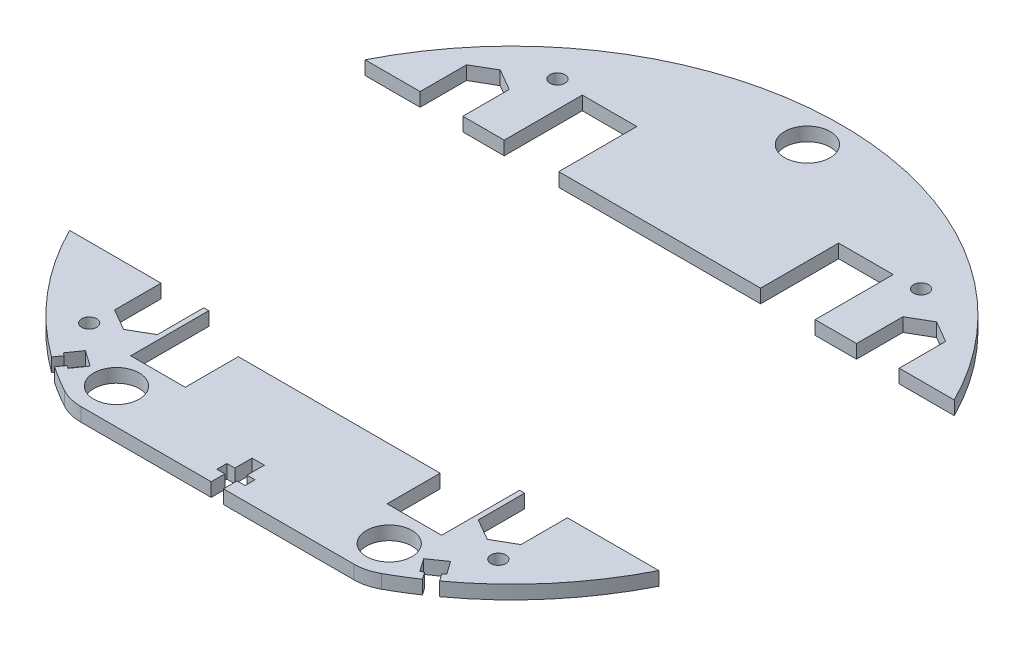
SolidWorks part; units mm, degrees
ref_plane "Front Plane" through (0, 0, 0) normal (0, 0, 1) x (1, 0, 0)
ref_plane "Top Plane" through (0, 0, 0) normal (0, 1, 0) x (1, 0, 0)
ref_plane "Right Plane" through (0, 0, 0) normal (1, 0, 0) x (0, 0, -1)
sketch "Sketch1" plane through (0, 0, 0) normal (0, 1, 0) x (1, 0, 0)
  line L0 (-30.03, -64.8129) -> (30.03, -64.8129)
  line L1 (0, -85) -> (0, 0) construction
  line L2 (0, -85) -> (32.4891, -64.8129) construction
  arc A0 (34.8348, -63.5829) -> (-34.8348, -63.5829) centre (0, 0) ccw
  circle A1 centre (0, -85) radius 38.25 construction
  arc A2 (30.03, -64.8129) -> (34.8348, -63.5829) centre (30.03, -54.8129) ccw
  arc A3 (-30.03, -64.8129) -> (-34.8348, -63.5829) centre (-30.03, -54.8129) cw
  dimension "D1" = 145
  dimension "D2" = 76.5
  dimension "D4" = 10
  dimension "D3" = 85
extrude "Boss-Extrude1" add sketch "Sketch1" along normal blind 3
sketch "Sketch2" plane through (0, 3, 0) normal (0, 1, 0) x (1, 0, 0)
  line L0 (18, -36.2) -> (-18, -36.2) construction
  line L1 (-34.2, -49.6757) -> (-22.2, -49.6757)
  line L2 (-34.2, -49.6757) -> (-34.2, 49.6757)
  line L3 (-34.2, 49.6757) -> (-22.2, 49.6757)
  line L4 (-22.2, -49.6757) -> (-22.2, -38)
  line L6 (-22.2, -49.6757) -> (-22.2, -38)
  line L8 (19, 28.2) -> (-19, 28.2) construction
  line L9 (22.2, -38) -> (-22.2, -38)
  line L10 (-19, 32.5) -> (-22.2, 32.5) construction
  line L11 (-19, 32.5) -> (-22.2, 32.5)
  line L12 (19, 28.2) -> (-19, 28.2)
  line L15 (-19, 32.5) -> (-19, 28.2)
  line L16 (-22.2, 32.5) -> (-22.2, 49.6757)
  line L17 (0, 0) -> (0, -64.8129) construction
  line L18 (-30.03, -64.8129) -> (30.03, -64.8129) construction
  line L19 (22.2, 32.5) -> (22.2, 49.6757)
  line L20 (19, 32.5) -> (19, 28.2)
  line L23 (19, 32.5) -> (22.2, 32.5)
  line L25 (22.2, -49.6757) -> (22.2, -38)
  line L26 (22.2, -49.6757) -> (22.2, -38)
  line L27 (34.2, 49.6757) -> (22.2, 49.6757)
  line L28 (34.2, -49.6757) -> (34.2, 49.6757)
  line L29 (34.2, -49.6757) -> (22.2, -49.6757)
  point P4 (27.4664, -36.2)
  dimension "D1" = 38
extrude "Cut-Extrude1" cut sketch "Sketch2" against normal through all
sketch "Sketch3" plane through (0, 3, 0) normal (0, 1, 0) x (1, 0, 0)
  line L0 (34.2, -32.5) -> (-34.2, -32.5)
  line L1 (-72.5, -32.5) -> (-34.2, -32.5)
  line L2 (-72.5, -32.5) -> (-72.5, 32.5)
  line L3 (-72.5, 32.5) -> (-34.2, 32.5)
  line L4 (72.5, -32.5) -> (72.5, 32.5)
  line L5 (-72.5, -32.5) -> (72.5, 32.5) construction
  line L6 (-72.5, 32.5) -> (72.5, -32.5) construction
  line L7 (-34.2, -49.6757) -> (-34.2, 49.6757) construction
  line L8 (34.2, 32.5) -> (-34.2, 32.5)
  line L9 (34.2, -49.6757) -> (34.2, 49.6757) construction
  line L10 (34.2, 32.5) -> (72.5, 32.5)
  line L11 (34.2, -32.5) -> (72.5, -32.5)
  arc A0 (34.8348, -63.5829) -> (-34.8348, -63.5829) centre (0, 0) ccw construction
  point P0 (0, 0)
  dimension "D1" = 65
extrude "Cut-Extrude2" cut sketch "Sketch3" against normal through all
sketch "Sketch4" plane through (0, 3, 0) normal (0, 1, 0) x (1, 0, 0)
  line L0 (0, 0) -> (0, -20.7985) construction
  circle A0 centre (30, -57) radius 5
  circle A4 centre (-30, -57) radius 5
  dimension "D3" = 10
  dimension "D1" = 57
  dimension "D2" = 30
extrude "Cut-Extrude3" cut sketch "Sketch4" against normal through all
sketch "Sketch5" plane through (0, 3, 0) normal (0, 1, 0) x (1, 0, 0)
  line L0 (-52.7, 37.2865) -> (-52.7, 32.5)
  line L2 (-34.2, 32.5) -> (-64.8074, 32.5) construction
  line L3 (-52.7, 32.5) -> (-43.3, 32.5)
  line L4 (-43.3, 32.5) -> (-43.3, 37.2865)
  line L6 (-44.7, -37.2865) -> (-44.7, -32.5)
  line L7 (-64.8074, -32.5) -> (-34.2, -32.5) construction
  line L8 (0, 0) -> (0, -64.8129) construction
  line L9 (-30.03, -64.8129) -> (30.03, -64.8129) construction
  line L16 (-35.3, -37.2865) -> (-35.3, -32.5)
  line L17 (-43.3, 42.7135) -> (-48, 45.4271)
  line L18 (-48, 45.4271) -> (-52.7, 42.7135)
  line L19 (-52.7, 42.7135) -> (-52.7, 37.2865)
  line L20 (-52.7, 37.2865) -> (-48, 34.5729) construction
  line L21 (-48, 34.5729) -> (-43.3, 37.2865) construction
  line L22 (-43.3, 37.2865) -> (-43.3, 42.7135)
  line L23 (-40, -34.5729) -> (-44.7, -37.2865) construction
  line L24 (-44.7, -37.2865) -> (-44.7, -42.7135)
  line L25 (-44.7, -42.7135) -> (-40, -45.4271)
  line L26 (-40, -45.4271) -> (-35.3, -42.7135)
  line L27 (-35.3, -42.7135) -> (-35.3, -37.2865)
  line L28 (-35.3, -37.2865) -> (-40, -34.5729) construction
  line L30 (-35.3, -32.5) -> (-44.7, -32.5)
  line L31 (35.3, -37.2865) -> (40, -34.5729) construction
  line L32 (40, -34.5729) -> (44.7, -37.2865) construction
  line L33 (48, 34.5729) -> (43.3, 37.2865) construction
  line L34 (52.7, 37.2865) -> (48, 34.5729) construction
  line L35 (35.3, -32.5) -> (44.7, -32.5)
  line L36 (35.3, -42.7135) -> (35.3, -37.2865)
  line L37 (40, -45.4271) -> (35.3, -42.7135)
  line L38 (44.7, -42.7135) -> (40, -45.4271)
  line L39 (44.7, -37.2865) -> (44.7, -42.7135)
  line L40 (43.3, 37.2865) -> (43.3, 42.7135)
  line L41 (52.7, 42.7135) -> (52.7, 37.2865)
  line L42 (48, 45.4271) -> (52.7, 42.7135)
  line L43 (43.3, 42.7135) -> (48, 45.4271)
  line L44 (35.3, -37.2865) -> (35.3, -32.5)
  line L45 (44.7, -37.2865) -> (44.7, -32.5)
  line L46 (43.3, 32.5) -> (43.3, 37.2865)
  line L47 (52.7, 32.5) -> (43.3, 32.5)
  line L48 (52.7, 37.2865) -> (52.7, 32.5)
  circle A2 centre (-48, 40) radius 4.7 construction
  circle A3 centre (-40, -40) radius 4.7 construction
  circle A4 centre (40, -40) radius 4.7 construction
  circle A5 centre (48, 40) radius 4.7 construction
  dimension "D1" = 9.4
  dimension "D2" = 48
  dimension "D3" = 40
  dimension "D4" = 40
  dimension "D5" = 40
  dimension "D6" = 9.4
extrude "Cut-Extrude4" cut sketch "Sketch5" against normal through all
sketch "Sketch7" plane through (0, 3, 0) normal (0, 1, 0) x (1, 0, 0)
  line L0 (0, 0) -> (0, 65) construction
  circle A0 centre (0, 65) radius 5
  dimension "D1" = 10
  dimension "D2" = 65
extrude "Cut-Extrude6" cut sketch "Sketch7" against normal through all
sketch "Sketch8" plane through (0, 3, 0) normal (0, 1, 0) x (1, 0, 0)
  line L0 (-1.35, -64.8129) -> (-1.35, -61.8129)
  line L1 (-30.03, -64.8129) -> (30.03, -64.8129) construction
  line L2 (-1.35, -61.8129) -> (-3.1, -61.8129)
  line L3 (-3.1, -61.8129) -> (-3.1, -59.6129)
  line L4 (-3.1, -59.6129) -> (-1.35, -59.6129)
  line L5 (-1.35, -59.6129) -> (-1.35, -55.8129)
  line L6 (-1.35, -55.8129) -> (1.35, -55.8129)
  line L7 (1.35, -55.8129) -> (1.35, -59.6129)
  line L8 (1.35, -59.6129) -> (3.1, -59.6129)
  line L9 (3.1, -59.6129) -> (3.1, -61.8129)
  line L10 (3.1, -61.8129) -> (1.35, -61.8129)
  line L11 (1.35, -61.8129) -> (1.35, -64.8129)
  line L12 (-1.35, -64.8129) -> (1.35, -64.8129)
  line L13 (-30.03, -64.8129) -> (30.03, -64.8129) construction
  point P18 (0, -64.8129)
  point P19 (0, -64.8129)
  dimension "D1" = 2.7
  dimension "D2" = 2.2
  dimension "D3" = 6.2
  dimension "D4" = 3
  dimension "D5" = 9
extrude "Cut-Extrude7" cut sketch "Sketch8" against normal through all
sketch "Sketch9" plane through (0, 3, 0) normal (0, 1, 0) x (1, 0, 0)
  line L0 (0, 0) -> (0, -27.4582) construction
  circle A0 centre (45, -48) radius 1.65
  circle A1 centre (-45, -48) radius 1.65
  circle A2 centre (40, 50) radius 1.65
  circle A3 centre (-40, 50) radius 1.65
  dimension "D3" = 3.3
  dimension "D1" = 45
  dimension "D2" = 48
  dimension "D4" = 40
  dimension "D5" = 50
extrude "Cut-Extrude8" cut sketch "Sketch9" against normal through all
sketch "Sketch10" plane through (0, 3, 0) normal (0, 1, 0) x (1, 0, 0)
  line L0 (0, 0) -> (0, -38) construction
  line L1 (-22.2, -38) -> (22.2, -38) construction
  line L2 (0, 0) -> (41.5843, -59.3885) construction
  line L3 (36.6889, -56.102) -> (40.1703, -53.6643)
  line L4 (36.6889, -56.102) -> (38.6964, -58.9691)
  line L5 (40.1703, -53.6643) -> (42.1778, -56.5314)
  line L6 (38.6964, -58.9691) -> (39.3313, -58.5245)
  line L7 (39.3313, -58.5245) -> (40.4784, -60.1629)
  line L8 (40.4784, -60.1629) -> (42.6901, -58.6142)
  line L9 (42.6901, -58.6142) -> (41.543, -56.9759)
  line L10 (41.543, -56.9759) -> (42.1778, -56.5314)
  line L11 (-41.543, -56.9759) -> (-42.1778, -56.5314)
  line L12 (-42.6901, -58.6142) -> (-41.543, -56.9759)
  line L13 (-40.4784, -60.1629) -> (-42.6901, -58.6142)
  line L14 (-39.3313, -58.5245) -> (-40.4784, -60.1629)
  line L15 (-38.6964, -58.9691) -> (-39.3313, -58.5245)
  line L16 (-40.1703, -53.6643) -> (-42.1778, -56.5314)
  line L17 (-36.6889, -56.102) -> (-38.6964, -58.9691)
  line L18 (-36.6889, -56.102) -> (-40.1703, -53.6643)
  arc A0 (34.8348, -63.5829) -> (64.8074, -32.5) centre (0, 0) ccw construction
  point P5 (38.4296, -54.8832)
  point P18 (41.5843, -59.3885)
  dimension "D1" = 35
  dimension "D2" = 4.25
  dimension "D3" = 3.5
  dimension "D4" = 2.7
  dimension "D5" = 2
extrude "Cut-Extrude9" cut sketch "Sketch10" against normal through all
equation "\"smallPulleyTeeth\"= 30"
equation "\"largePulleyTeeth\"= 30"
equation "\"eighthThick\"= 3.0mm"
equation "\"sixteenthThick\" = 1.7mm"
equation "\"quarterThick\"=6.0mm"
equation "\"OD\" = 145mm"
equation "\"puckAngle\" = 60.5deg"
equation "\"puckDiam\" = 76.5mm"
equation "\"axlePress\" = 5.9mm"
equation "\"press\" = 0.2mm"
equation "\"wheelClear\" = 0.3mm"
equation "\"10-32clear\" = 4.8mm"
equation "\"6-32clear\" = 3.3mm"
equation "\"8-32clear\" = 4.0mm"
equation "\"4-40clear\" = 3.0mm"
equation "\"wheelHeight\" = 22mm"
equation "\"wheelWell\" = 65mm"
equation "\"D1@Sketch1\"=\"OD\""
equation "\"D1@Boss-Extrude1\"=\"eighthThick\""
equation "\"D2@Sketch1\"=\"puckDiam\""
equation "\"D1@Sketch3\"=\"wheelWell\""
equation "\"puckDist\" = 85mm"
equation "\"scoopFillet\" = 5mm"
equation "\"10-32tap\" = 4.45mm"
equation "\"ledSmall\" = 3.1mm"
equation "\"ledLarge\" = 4.2mm"
equation "\"ledLength\" = 4.2mm"
equation "\"D3@Sketch1\"=\"puckDist\""
equation "\"4-40close\" = 2.7mm"
equation "\"4-40nutThick\" = 2.2mm"
equation "\"4-40nutWidth\" = 6.2mm"
equation "\"D1@Sketch8\"=\"4-40close\""
equation "\"D3@Sketch8\"=\"4-40nutWidth\""
equation "\"D3@Sketch9\"=\"6-32clear\""
equation "\"4-40insertHeight\" = 3.5mm"
equation "\"4-40insert\" = 4.25mm"
equation "\"D2@Sketch10\"=\"4-40insert\""
equation "\"D3@Sketch10\"=\"4-40insertHeight\""
equation "\"D4@Sketch10\"=\"4-40close\""
